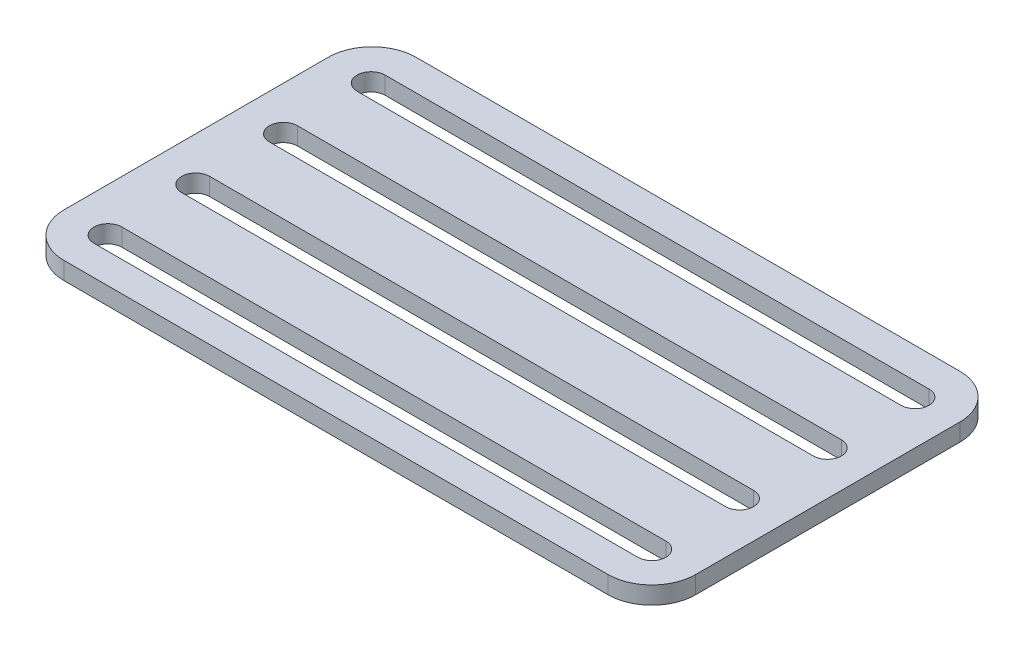
SolidWorks part; units mm, degrees
ref_plane "前视基准面" through (0, 0, 0) normal (0, 0, 1) x (1, 0, 0)
ref_plane "上视基准面" through (0, 0, 0) normal (0, 1, 0) x (1, 0, 0)
ref_plane "右视基准面" through (0, 0, 0) normal (1, 0, 0) x (0, 0, -1)
other "Configuration Table"
sketch "草图1" plane through (0, 0, 0) normal (0, 1, 0) x (1, 0, 0)
  line L0 (0, 452.0543) -> (0, 40.1167) construction
  line L1 (-31, 5) -> (0, 5) construction
  line L2 (31, 40.1167) -> (-31, 40.1167)
  line L4 (31, 0) -> (-31, 0)
  line L5 (-36, 35.1167) -> (-36, 5)
  line L6 (-31, 6.6) -> (0, 6.6)
  line L7 (-31, 3.4) -> (0, 3.4)
  line L8 (-31, 15) -> (0, 15) construction
  line L9 (-31, 16.6) -> (0, 16.6)
  line L10 (-31, 13.4) -> (0, 13.4)
  line L11 (-31, 25) -> (0, 25) construction
  line L12 (-31, 26.6) -> (0, 26.6)
  line L13 (-31, 23.4) -> (0, 23.4)
  line L14 (-31, 35) -> (0, 35) construction
  line L15 (-31, 36.6) -> (0, 36.6)
  line L16 (-31, 33.4) -> (0, 33.4)
  line L17 (36, 35.1167) -> (36, 5)
  line L18 (31, 35) -> (0, 35) construction
  line L19 (31, 36.6) -> (0, 36.6)
  line L20 (31, 33.4) -> (0, 33.4)
  line L21 (31, 25) -> (0, 25) construction
  line L22 (31, 26.6) -> (0, 26.6)
  line L23 (31, 23.4) -> (0, 23.4)
  line L24 (31, 15) -> (0, 15) construction
  line L25 (31, 16.6) -> (0, 16.6)
  line L26 (31, 13.4) -> (0, 13.4)
  line L27 (31, 5) -> (0, 5) construction
  line L28 (31, 6.6) -> (0, 6.6)
  line L29 (31, 3.4) -> (0, 3.4)
  line L32 (0, 0) -> (0, -431.8668) construction
  arc A0 (-31, 40.1167) -> (-36, 35.1167) centre (-31, 35.1167) ccw
  arc A1 (-31, 0) -> (-36, 5) centre (-31, 5) cw
  arc A2 (-31, 6.6) -> (-31, 3.4) centre (-31, 5) ccw
  arc A4 (-31, 16.6) -> (-31, 13.4) centre (-31, 15) ccw
  arc A6 (-31, 26.6) -> (-31, 23.4) centre (-31, 25) ccw
  arc A8 (-31, 36.6) -> (-31, 33.4) centre (-31, 35) ccw
  arc A10 (31, 0) -> (36, 5) centre (31, 5) ccw
  arc A11 (31, 40.1167) -> (36, 35.1167) centre (31, 35.1167) cw
  arc A12 (31, 36.6) -> (31, 33.4) centre (31, 35) cw
  arc A14 (31, 26.6) -> (31, 23.4) centre (31, 25) cw
  arc A16 (31, 16.6) -> (31, 13.4) centre (31, 15) cw
  arc A18 (31, 6.6) -> (31, 3.4) centre (31, 5) cw
  point P11 (-15.5, 5)
  point P20 (-15.5, 15)
  point P27 (-15.5, 25)
  point P34 (-15.5, 35)
  point P46 (15.5, 35)
  point P53 (15.5, 25)
  point P60 (15.5, 15)
  point P66 (15.5, 5)
  dimension "D2" = 5
extrude "凸台-拉伸1" add sketch "草图1" along normal blind 2
